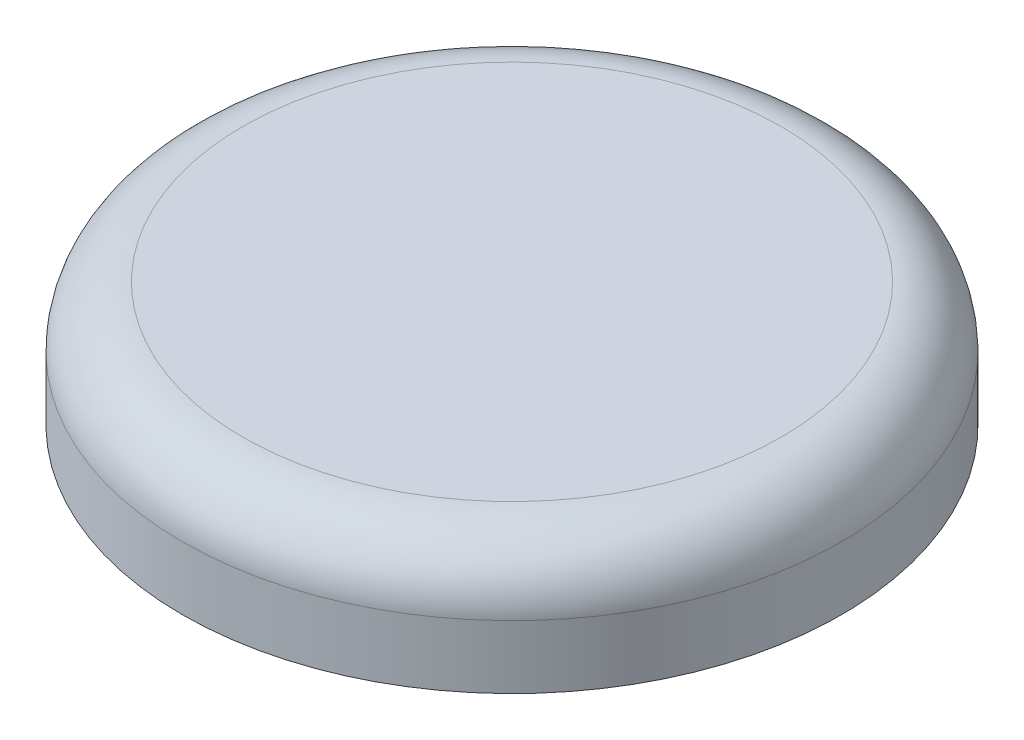
SolidWorks part; units mm, degrees
ref_plane "Front Plane" through (0, 0, 0) normal (0, 0, 1) x (1, 0, 0)
ref_plane "Top Plane" through (0, 0, 0) normal (0, 1, 0) x (1, 0, 0)
ref_plane "Right Plane" through (0, 0, 0) normal (1, 0, 0) x (0, 0, -1)
sketch "Sketch1" plane through (0, 0, 0) normal (0, 0, 1) x (1, 0, 0)
  line L0 (0, 0) -> (-62.23, 0)
  line L1 (-71.12, -8.89) -> (-71.12, -10.795)
  line L2 (-71.12, -10.795) -> (-73.66, -10.795)
  line L3 (-73.66, -10.795) -> (-73.66, -23.495)
  line L4 (-73.66, -23.495) -> (-76.2, -23.495)
  line L5 (-76.2, -23.495) -> (-76.2, -8.89)
  line L6 (0, 0) -> (0, 5.08)
  line L7 (0, 5.08) -> (-62.23, 5.08)
  line L8 (0, 0) -> (0, -23.495) construction
  line L9 (0, -23.495) -> (-73.66, -23.495) construction
  line L10 (-76.2, -23.495) -> (-76.2, -80.645) construction
  arc A0 (-62.23, 0) -> (-71.12, -8.89) centre (-62.23, -8.89) ccw
  arc A1 (-62.23, 5.08) -> (-76.2, -8.89) centre (-62.23, -8.89) ccw
  dimension "D7" = 8.89
  dimension "D1" = 2.54
  dimension "D2" = 5.08
  dimension "D3" = 5.08
  dimension "D5" = 12.7
  dimension "D6" = 28.575
revolve "Revolve1" add sketch "Sketch1" angle 360 about L6
